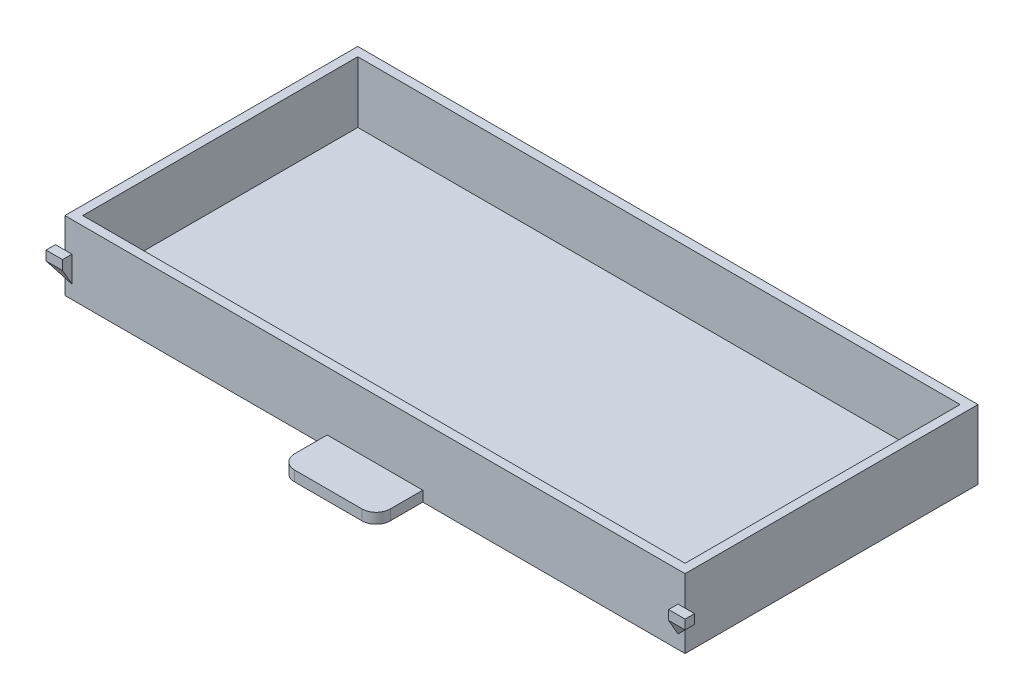
SolidWorks part; units mm, degrees
ref_plane "Front Plane" through (0, 0, 0) normal (0, 0, 1) x (1, 0, 0)
ref_plane "Top Plane" through (0, 0, 0) normal (0, 1, 0) x (1, 0, 0)
ref_plane "Right Plane" through (0, 0, 0) normal (1, 0, 0) x (0, 0, -1)
sketch "Sketch2" plane through (0, 0, 0) normal (0, 1, 0) x (1, 0, 0)
  line L0 (0, 31.1) -> (0, -31.1) construction
  line L1 (-65.85, 31.1) -> (65.85, 31.1)
  line L2 (-65.85, 31.1) -> (-65.85, -31.1)
  line L3 (-65.85, -31.1) -> (65.85, -31.1)
  line L4 (65.85, 31.1) -> (65.85, -31.1)
  line L5 (-65.85, 0) -> (65.85, 0) construction
  point P8 (0, 0)
  dimension "D1" = 131.7
  dimension "D2" = 62.2
extrude "Boss-Extrude1" add sketch "Sketch2" along normal blind 14.7
sketch "Sketch3" plane through (0, 14.7, 0) normal (0, 1, 0) x (1, 0, 0)
  line L0 (-65.85, 31.1) -> (-65.85, -31.1) construction
  line L1 (-63.95, 29.2) -> (63.95, 29.2)
  line L2 (-63.95, 29.2) -> (-63.95, -29.2)
  line L3 (-63.95, -29.2) -> (63.95, -29.2)
  line L4 (63.95, 29.2) -> (63.95, -29.2)
  line L5 (-65.85, -31.1) -> (65.85, -31.1) construction
  line L6 (65.85, 31.1) -> (-65.85, 31.1) construction
  line L7 (65.85, -31.1) -> (65.85, 31.1) construction
  dimension "D1" = 1.9
  dimension "D2" = 1.9
  dimension "D3" = 1.9
  dimension "D4" = 1.9
extrude "Cut-Extrude1" cut sketch "Sketch3" against normal blind 13
sketch "Sketch4" plane through (0, 0, 0) normal (0, -1, 0) x (1, 0, 0)
  line L0 (0, 31.1) -> (0, -31.1) construction
  line L1 (-65.85, 31.1) -> (65.85, 31.1) construction
  line L2 (65.85, -31.1) -> (-65.85, -31.1) construction
  line L4 (-10.15, 31.1) -> (10.15, 31.1)
  line L5 (-10.15, 31.1) -> (-10.15, 41)
  line L6 (-10.15, 41) -> (10.15, 41)
  line L7 (10.15, 31.1) -> (10.15, 41)
  dimension "D1" = 20.3
  dimension "D2" = 10.15
  dimension "D3" = 9.9
extrude "Boss-Extrude2" add sketch "Sketch4" against normal blind 2.2
fillet "Fillet1" radius 3 2 edges at (-10.15, 1.1, 41) (10.15, 1.1, 41)
sketch "Sketch5" plane through (0, 0, 31.1) normal (0, 0, 1) x (1, 0, 0)
  line L0 (-65.85, 14.7) -> (-65.85, 0) construction
  line L1 (-65.85, 8.35) -> (-67.85, 8.35)
  line L2 (-65.85, 8.35) -> (-65.85, 6.35)
  line L3 (-65.85, 6.35) -> (-67.85, 6.35)
  line L4 (-67.85, 8.35) -> (-67.85, 6.35)
  line L5 (-67.85, 6.35) -> (-65.85, 4.35)
  line L6 (-65.85, 4.35) -> (-65.85, 6.35)
  line L7 (-65.85, 14.7) -> (65.85, 14.7) construction
  line L8 (-64.35, 6.35) -> (-64.35, 2.85)
  line L9 (-65.85, 8.35) -> (-64.35, 8.35)
  line L10 (-65.85, 8.35) -> (-65.85, 6.35)
  line L11 (-65.85, 6.35) -> (-64.35, 6.35)
  line L12 (-64.35, 8.35) -> (-64.35, 6.35)
  line L13 (-64.35, 2.85) -> (-65.85, 4.35)
  line L14 (-65.85, 6.35) -> (-64.35, 6.35)
  line M13 (-65.85, 14.7) -> (-65.85, 0)
  dimension "D1" = 2
  dimension "D2" = 2
  dimension "D3" = 6.35
  dimension "D4" = 3.5
extrude "Boss-Extrude3" add sketch "Sketch5" along normal blind 2 contours L12 L9 L11 M13 | L1 L4 L3 M13 | L3 L5 M13 | L13 L8 L11 M13
mirror "Mirror1" about plane through (0, 0, 0) normal (1, 0, 0) of "Boss-Extrude3"
sketch "Sketch6" plane through (-65.85, 0, 0) normal (-1, 0, 0) x (0, 0, 1)
  line L0 (33.1, 6.35) -> (31.1, 2.85)
  line L1 (31.1, 2.85) -> (33.1, 2.85)
  line L2 (33.1, 2.85) -> (33.1, 6.35)
extrude "Cut-Extrude2" cut sketch "Sketch6" against normal mid plane 400
equation "\"D3@Sketch3\"=\"D1@Sketch3\""
equation "\"D4@Sketch3\"=\"D1@Sketch3\""
equation "\"D2@Sketch4\"=\"D1@Sketch4\"/2"
equation "\"D3@Sketch5\"=(14.7-2)/2"
